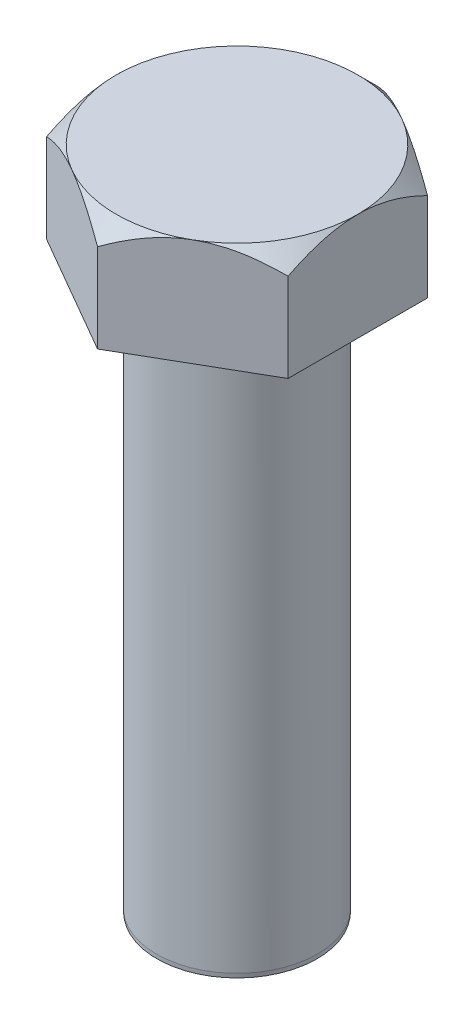
SolidWorks part; units mm, degrees
ref_plane "Front Plane" through (0, 0, 0) normal (0, 0, 1) x (1, 0, 0)
ref_plane "Top Plane" through (0, 0, 0) normal (0, 1, 0) x (1, 0, 0)
ref_plane "Right Plane" through (0, 0, 0) normal (1, 0, 0) x (0, 0, -1)
sketch "Sketch1" plane through (0, 0, 0) normal (0, 1, 0) x (1, 0, 0)
  line L1 (0, 8.2562) -> (-7.1501, 4.1281)
  line L2 (-7.1501, 4.1281) -> (-7.1501, -4.1281)
  line L3 (-7.1501, -4.1281) -> (0, -8.2562)
  line L4 (0, -8.2562) -> (7.1501, -4.1281)
  line L5 (7.1501, -4.1281) -> (7.1501, 4.1281)
  line L6 (7.1501, 4.1281) -> (0, 8.2562)
  circle A0 centre (0, 0) radius 7.1501 construction
  dimension "D1" = 14.3002
extrude "Boss-Extrude1" add sketch "Sketch1" along normal blind 6.35
sketch "Sketch2" plane through (0, 0, 0) normal (0, -1, 0) x (1, 0, 0)
  circle A0 centre (0, 0) radius 4.7625
  dimension "D1" = 9.525
extrude "Boss-Extrude2" add sketch "Sketch2" along normal blind 33.02
cosmetic thread "Cosmetic Thread1" parameters "D2"=8.2652
sketch "Sketch3" plane through (0, 6.35, 0) normal (0, 1, 0) x (1, 0, 0)
  circle A0 centre (0, 0) radius 7.1501
extrude "Cut-Extrude1" cut sketch "Sketch3" against normal blind 20.32 draft 45 flip side to cut
chamfer "Chamfer1" distance 0.254 angle 5 1 edges at (0, -33.02, -4.7625)
